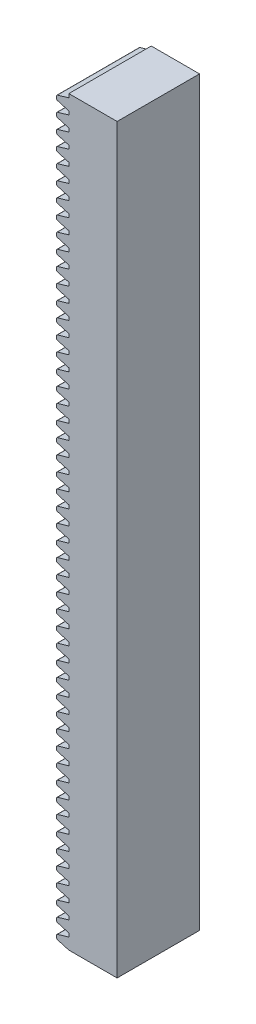
SolidWorks part; units mm, degrees
ref_plane "Front Plane" through (0, 0, 0) normal (0, 0, 1) x (1, 0, 0)
ref_plane "Top Plane" through (0, 0, 0) normal (0, 1, 0) x (1, 0, 0)
ref_plane "Right Plane" through (0, 0, 0) normal (1, 0, 0) x (0, 0, -1)
sketch "Sketch1" plane through (0, 0, 0) normal (0, 0, 1) x (1, 0, 0)
  line L0 (15.0694, -11.3934) -> (12.3219, -12.1906)
  line L1 (15.0694, -10.4934) -> (26.7872, -10.4934)
  line L2 (15.0694, -10.4934) -> (15.0694, -11.3934)
  line L3 (15.1192, -14.1343) -> (26.7872, -14.1343)
  line L4 (26.7872, -10.4934) -> (26.7872, -14.1343)
  line L5 (12.0694, -12.5267) -> (12.0694, -13.001)
  line L6 (15.0216, -14.1204) -> (12.3219, -13.3371)
  line L7 (12.2353, -12.7639) -> (12.6753, -12.7639) construction
  arc A1 (15.0216, -14.1204) -> (15.1192, -14.1343) centre (15.1192, -13.7843) ccw
  arc A2 (12.0694, -13.001) -> (12.3219, -13.3371) centre (12.4194, -13.001) ccw
  arc A3 (12.3219, -12.1906) -> (12.0694, -12.5267) centre (12.4194, -12.5267) ccw
  point P6 (15.0694, -14.1343)
  point P10 (12.0694, -13.2639)
  point P14 (12.0694, -12.2639)
  dimension "D2" = 16.18
  dimension "D5" = 11.6681
  dimension "D1" = 1
  dimension "D3" = 0.9
  dimension "D4" = 3
extrude "Boss-Extrude1" add sketch "Sketch1" along normal blind 20
pattern_linear "LPattern1" count 50 spacing 3.6 along (0, 1, 0) of "Boss-Extrude1"
